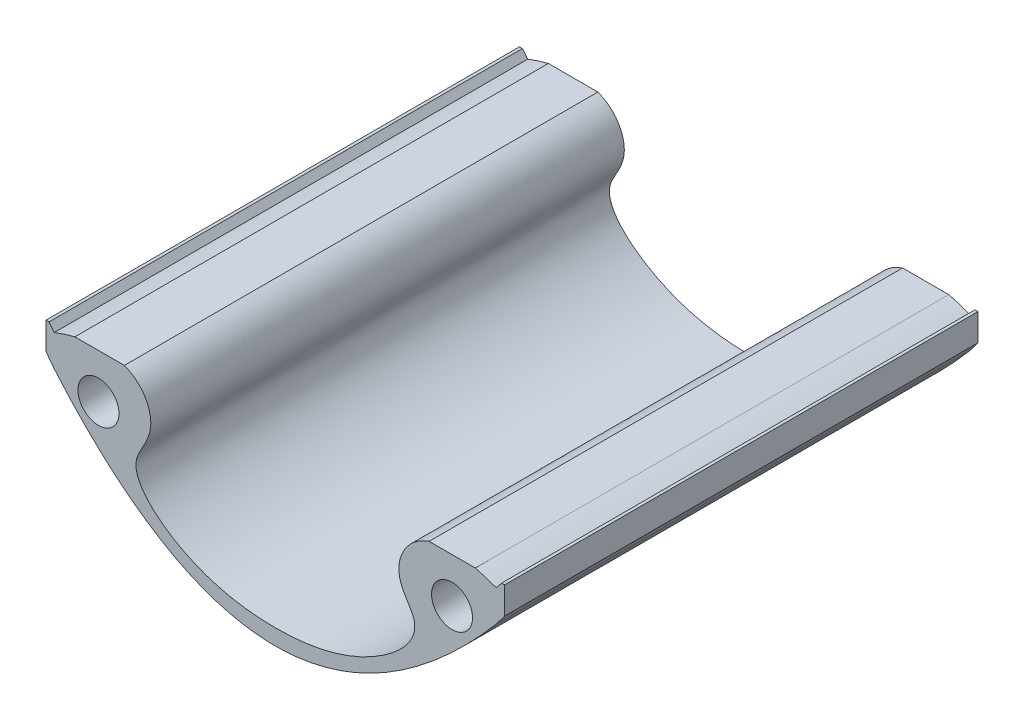
SolidWorks part; units mm, degrees
material "Balsa"
ref_plane "Front Plane" through (0, 0, 0) normal (0, 0, 1) x (1, 0, 0)
ref_plane "Top Plane" through (0, 0, 0) normal (0, 1, 0) x (1, 0, 0)
ref_plane "Right Plane" through (0, 0, 0) normal (1, 0, 0) x (0, 0, -1)
sketch "草圖1" plane through (0, 0, 0) normal (0, 0, 1) x (1, 0, 0)
  line L0 (0, 0) -> (-23.551, 0) construction
  line L1 (-35, 1) -> (0, -40) construction
  line L2 (0, -40) -> (35, 1) construction
  line L3 (-35, 1) -> (-65, 40) construction
  line L4 (-65, 40) -> (-40, 80) construction
  line L5 (35, 1) -> (65, 40) construction
  line L6 (65, 40) -> (40, 80) construction
  line L7 (-35, 6) -> (-63, 40) construction
  line L8 (-63, 40) -> (-38, 80) construction
  line L9 (35, 6) -> (63, 40) construction
  line L10 (63, 40) -> (38, 80) construction
  line L11 (-40, 80) -> (-38, 80)
  line L12 (38, 80) -> (40, 80)
  circle A0 centre (-28, 0) radius 3.25
  circle A1 centre (28, 0) radius 3.25
  circle A2 centre (0, 80) radius 3.25 construction
  spline S0 degree 2 poles (-35, 1) (0, -40) (35, 1) knots 0 0 0 1 1 1
  spline S1 degree 3 poles (-35, 6) (-23.9127, 10.2115) (-16.8625, 0.9167) (-25.2122, -5.9777) (-14.4761, -15.3053) (0.0184, -17.8304) (14.4017, -15.3383) (25.4357, -5.864) (16.5044, 0.5434) (24.2922, 10.071) (35, 6) knots 0 0 0 0 0.105196 0.200517 0.353332 0.503002 0.652672 0.805487 0.900808 1 1 1 1
  spline S2 degree 2 poles (-35, 1) (-65, 40) (-40, 80) knots 0 0 0 1 1 1
  spline S3 degree 2 poles (35, 1) (65, 40) (40, 80) knots 0 0 0 1 1 1
  spline S4 degree 2 poles (-35, 6) (-63, 40) (-38, 80) knots 0 0 0 1 1 1
  spline S5 degree 2 poles (35, 6) (63, 40) (38, 80) knots 0 0 0 1 1 1
  dimension "D1" = 6.5
  dimension "D12" = 17
  dimension "D2" = 28
  dimension "D3" = 28
  dimension "D4" = 35
  dimension "D5" = 35
  dimension "D6" = 40
  dimension "D7" = 20
  dimension "D8" = 22
  dimension "D9" = 5
  dimension "D10" = 14
  dimension "D11" = 14
  dimension "D13" = 14
  dimension "D14" = 22
  dimension "D15" = 20
  dimension "D16" = 35
  dimension "D17" = 35
  dimension "D18" = 6
  dimension "D19" = 80
  dimension "D20" = 40
  dimension "D21" = 80
  dimension "D22" = 40
  dimension "D23" = 65
  dimension "D24" = 65
  dimension "D25" = 40
  dimension "D26" = 2
  dimension "D27" = 2
  dimension "D28" = 2
  dimension "D29" = 2
  dimension "D30" = 1
  dimension "D31" = 3
extrude "填料-伸長1" add sketch "草圖1" along normal blind 75
sketch "草圖2" plane through (0, 0, 0) normal (1, 0, 0) x (0, 0, -1)
  line L0 (-75, 80) -> (0, 80) construction
  line L1 (-87.5483, 80) -> (5.1689, 80)
  line L2 (-87.5483, 80) -> (-87.5483, 7.0395)
  line L3 (-87.5483, 7.0395) -> (5.1689, 7.0395)
  line L4 (5.1689, 80) -> (5.1689, 7.0395)
extrude "除料-伸長1" cut sketch "草圖2" against normal through all and the other way through all
sketch "草圖3" plane through (0, 7.0395, 0) normal (0, 1, 0) x (1, 0, 0)
  line L0 (-39.3121, -75) -> (-39.3121, 0) construction
  line L1 (36.3121, 12.7627) -> (66.8908, 12.7627)
  line L2 (36.3121, 12.7627) -> (36.3121, -97.7627)
  line L3 (36.3121, -97.7627) -> (66.8908, -97.7627)
  line L4 (66.8908, 12.7627) -> (66.8908, -97.7627)
  line L5 (-36.3121, 22.5258) -> (-58.0488, 22.5258)
  line L6 (-36.3121, 22.5258) -> (-36.3121, -104.9469)
  line L7 (-36.3121, -104.9469) -> (-58.0488, -104.9469)
  line L8 (-58.0488, 22.5258) -> (-58.0488, -104.9469)
  line L9 (39.3121, 0) -> (39.3121, -75) construction
  dimension "D1" = 3
  dimension "D2" = 3
extrude "除料-伸長2" cut sketch "草圖3" against normal through all
